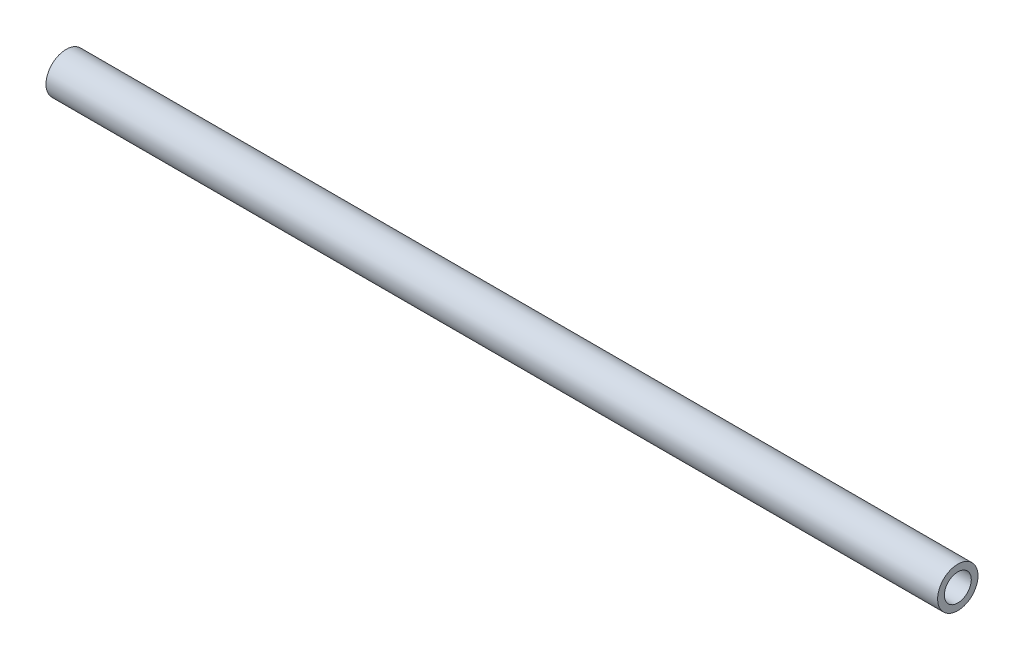
SolidWorks part; units mm, degrees
ref_plane "Front Plane" through (0, 0, 0) normal (0, 0, 1) x (1, 0, 0)
ref_plane "Top Plane" through (0, 0, 0) normal (0, 1, 0) x (1, 0, 0)
ref_plane "Right Plane" through (0, 0, 0) normal (1, 0, 0) x (0, 0, -1)
sketch "Sketch1" plane through (0, 0, 0) normal (0, 0, 1) x (1, 0, 0)
  line L0 (0, 0) -> (8000, 0) construction
  line L1 (900, 80) -> (900, 120)
  line L2 (900, 120) -> (6200, 120)
  line L3 (6200, 120) -> (6200, 80)
  line L4 (6200, 80) -> (900, 80)
revolve "Revolve1" add sketch "Sketch1" angle 360 about L0
